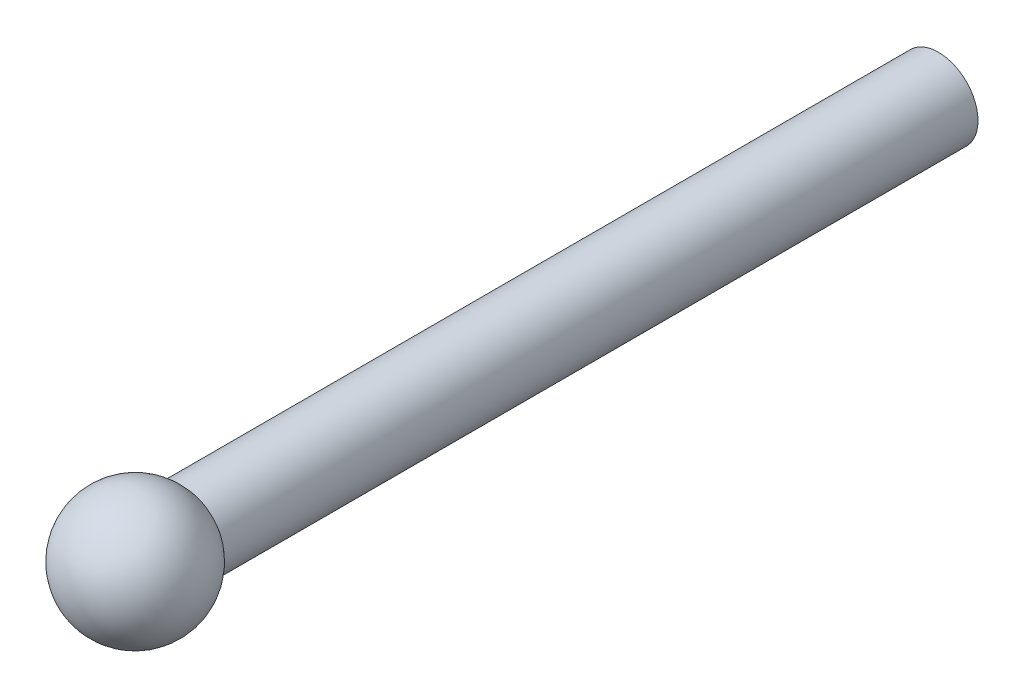
SolidWorks part; units mm, degrees
material "ABS"
ref_plane "Front Plane" through (0, 0, 0) normal (0, 0, 1) x (1, 0, 0)
ref_plane "Top Plane" through (0, 0, 0) normal (0, 1, 0) x (1, 0, 0)
ref_plane "Right Plane" through (0, 0, 0) normal (1, 0, 0) x (0, 0, -1)
sketch "Sketch4" plane through (0, 0, 0) normal (0, 0, 1) x (1, 0, 0)
  circle A0 centre (0, 0) radius 1.5
  dimension "D1" = 3
extrude "Boss-Extrude4" add sketch "Sketch4" against normal blind 30
ref_plane "Plane1" through (0, 0, 0.5) normal (0, 0, 1) x (1, 0, 0)
sketch "Sketch6" plane through (0, 0, 0.5) normal (0, 0, 1) x (1, 0, 0)
  line L0 (0, 0) -> (0, -2.4)
  line L1 (0, -2.4) -> (0, 2.4)
  circle A0 centre (0, 0) radius 2.4 construction
  arc A1 (0, 2.4) -> (0, -2.4) centre (0, 0) cw
  dimension "D1" = 4.8
revolve "Revolve1" add sketch "Sketch6" angle 360 about L1
